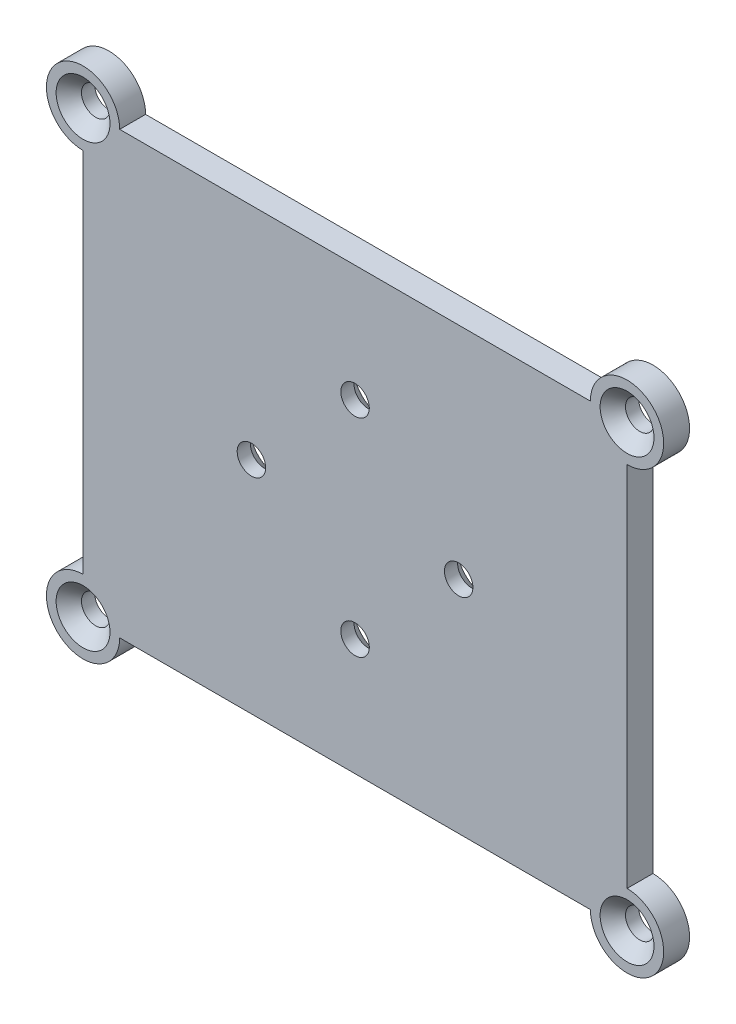
SolidWorks part; units mm, degrees
material "6061 Alloy"
ref_plane "Front Plane" through (0, 0, 0) normal (1, 0, 0) x (0, 1, 0)
ref_plane "Top Plane" through (0, 0, 0) normal (0, 0, 1) x (0, 1, 0)
ref_plane "Right Plane" through (0, 0, 0) normal (0, 1, 0) x (-1, 0, 0)
sketch "Sketch1" plane through (0, 0, 0) normal (0, 0, 1) x (0, 1, 0)
  line L0 (0, 0) -> (0, 20) construction
  line L1 (-37.5, -47.5) -> (37.5, -47.5)
  line L2 (-37.5, -47.5) -> (-37.5, 47.5)
  line L3 (-37.5, 47.5) -> (37.5, 47.5)
  line L4 (37.5, -47.5) -> (37.5, 47.5)
  line L5 (-37.5, -47.5) -> (37.5, 47.5) construction
  line L6 (-37.5, 47.5) -> (37.5, -47.5) construction
  circle A0 centre (0, 20) radius 1
  circle A1 centre (20, 0) radius 1
  circle A2 centre (0, -20) radius 1
  circle A3 centre (-20, 0) radius 1
  point P0 (0, 0)
  point P18 (0, 0)
  dimension "D3" = 2
  dimension "D4" = 20
  dimension "D1" = 95
  dimension "D2" = 75
  dimension "D5" = 4
extrude "Boss-Extrude1" add sketch "Sketch1" along normal blind 5
hole_wizard "CSK for M5 Flat Head Machine Screw1" positions "3DSketch1" profile "Sketch2" countersink size "M5" standard "ANSI Metric" end condition through all
sketch3d "3DSketch1"
  line L0 (0, 20, 5) -> (0, 20, 0) construction
  line L1 (-20, 0, 5) -> (-20, 0, 0) construction
  line L2 (0, -20, 5) -> (0, -20, 0) construction
  line L3 (20, 0, 5) -> (20, 0, 0) construction
  point P0 (0, 20, 0)
  point P4 (-20, 0, 0)
  point P8 (0, -20, 0)
  point P12 (20, 0, 0)
sketch "Sketch2" plane through (0, 20, 0) normal (1, 0, 0) x (0, 1, 0)
  line L0 (0, 0) -> (0, 5)
  line L1 (0, 5) -> (2.75, 5)
  line L2 (2.75, 5) -> (2.75, 2.45)
  line L3 (2.75, 2.45) -> (5.2, 0)
  line L5 (5.2, 0) -> (0, 0)
  line L6 (-2.75, 2.45) -> (-5.2, 0) construction
  line L11 (0, -6.35) -> (0, 107.95) construction
  dimension "Thru Hole Dia." = 5.5
  dimension "Thru Hole Depth" = 5
  dimension "Near C'Sink Dia." = 10.4
  dimension "Near C'Sink Angle" = 90
sketch "Sketch3" plane through (0, 0, 5) normal (0, 0, 1) x (1, 0, 0)
  line L0 (47.5, 37.5) -> (-47.5, 37.5) construction
  line L1 (-52.5, -42.5) -> (52.5, -42.5)
  line L2 (-52.5, -42.5) -> (-52.5, 42.5)
  line L3 (-52.5, 42.5) -> (52.5, 42.5)
  line L4 (52.5, -42.5) -> (52.5, 42.5)
  line L5 (-52.5, -42.5) -> (52.5, 42.5) construction
  line L6 (-52.5, 42.5) -> (52.5, -42.5) construction
  line L7 (-47.5, 37.5) -> (-47.5, -37.5) construction
  line L9 (-47.5, -37.5) -> (47.5, -37.5)
  line L10 (-47.5, -37.5) -> (-47.5, 37.5)
  line L11 (-47.5, 37.5) -> (47.5, 37.5)
  line L12 (47.5, -37.5) -> (47.5, 37.5)
  line L13 (-47.5, -37.5) -> (47.5, 37.5) construction
  line L14 (-47.5, 37.5) -> (47.5, -37.5) construction
  circle A0 centre (-52.5, 42.5) radius 7.0711
  circle A1 centre (52.5, 42.5) radius 7.0711
  circle A2 centre (52.5, -42.5) radius 7.0711
  circle A3 centre (-52.5, -42.5) radius 7.0711
  point P0 (0, 0)
  point P18 (0, 0)
  line M7 (47.5, 37.5) -> (-47.5, 37.5)
  line M8 (-47.5, 37.5) -> (-47.5, -37.5)
  line M9 (-47.5, -37.5) -> (47.5, -37.5)
  line M10 (47.5, -37.5) -> (47.5, 37.5)
  dimension "D1" = 5
  dimension "D2" = 5
extrude "Boss-Extrude2" add sketch "Sketch3" against normal blind 5 contours L3 A0 L2 | L2 A0 L3 | A1 L3 A0 M7 | L4 A1 L3 | L3 A1 L4 | A2 L4 A1 M10 | L4 A2 L1 | L1 A2 L4 | A3 L1 A2 M9 | L1 A3 L2 | L2 A3 L1 | A3 A0 L2 M8
sketch "Sketch4" plane through (0, 0, 5) normal (0, 0, 1) x (1, 0, 0)
  point P0 (-52.5, 42.5)
  point P1 (52.5, 42.5)
  point P3 (52.5, -42.5)
  point P5 (-52.5, -42.5)
hole_wizard "CSK for M5 Flat Head Machine Screw2" positions "Sketch4" profile "Sketch5" countersink size "M5" standard "ANSI Metric" end condition through all
sketch "Sketch5" plane through (-52.5, 42.5, 5) normal (1, 0, 0) x (0, -1, 0)
  line L0 (0, 0) -> (0, 5)
  line L1 (0, 5) -> (2.75, 5)
  line L2 (2.75, 5) -> (2.75, 2.45)
  line L3 (2.75, 2.45) -> (5.2, 0)
  line L5 (5.2, 0) -> (0, 0)
  line L6 (-2.75, 2.45) -> (-5.2, 0) construction
  line L11 (0, -6.35) -> (0, 107.95) construction
  dimension "Thru Hole Dia." = 5.5
  dimension "Thru Hole Depth" = 5
  dimension "Near C'Sink Dia." = 10.4
  dimension "Near C'Sink Angle" = 90
